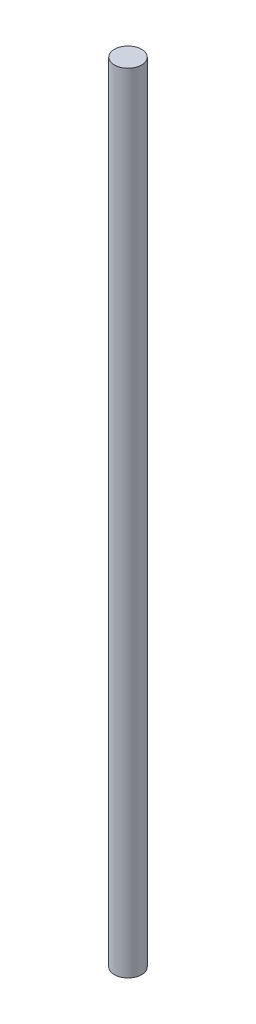
SolidWorks part; units mm, degrees
ref_plane "Front Plane" through (0, 0, 0) normal (0, 0, 1) x (1, 0, 0)
ref_plane "Top Plane" through (0, 0, 0) normal (0, 1, 0) x (1, 0, 0)
ref_plane "Right Plane" through (0, 0, 0) normal (1, 0, 0) x (0, 0, -1)
sketch "Sketch1" plane through (0, 0, 0) normal (0, 1, 0) x (1, 0, 0)
  circle A0 centre (0, 0) radius 2.25
  dimension "D1" = 4.5
extrude "Boss-Extrude1" add sketch "Sketch1" along normal blind 130
